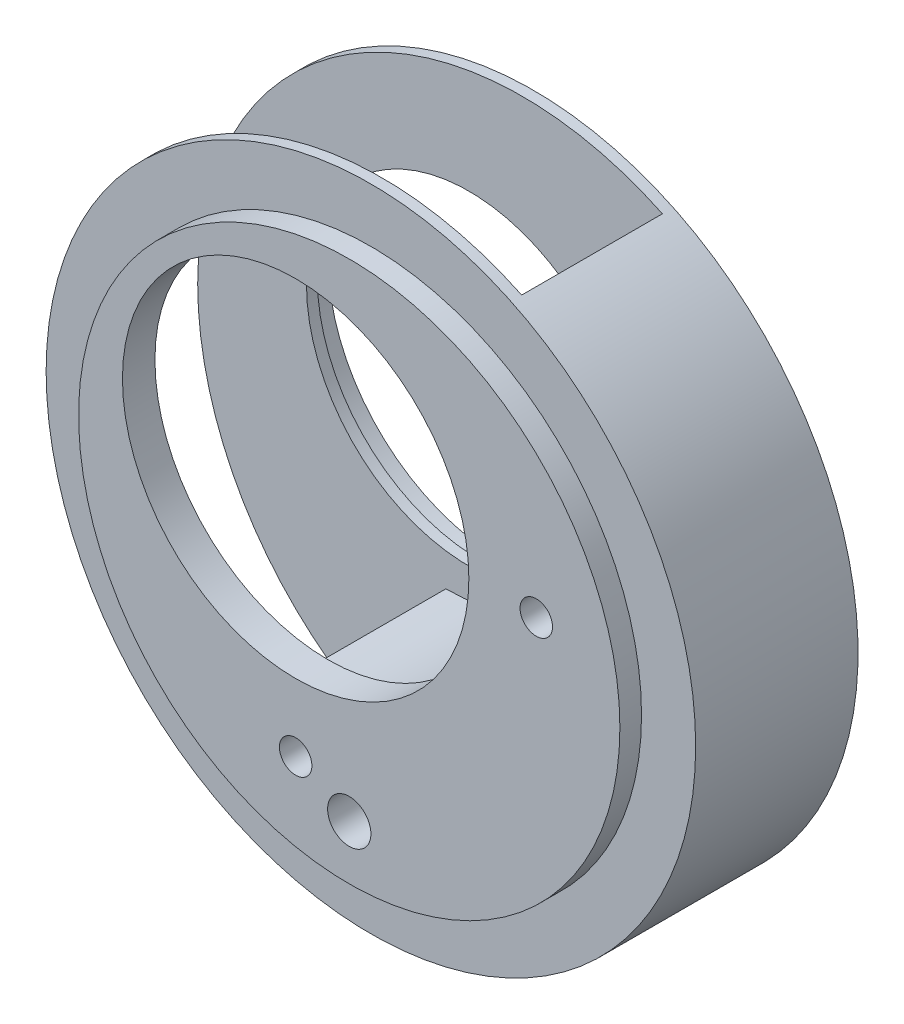
SolidWorks part; units mm, degrees
ref_plane "前视基准面" through (0, 0, 0) normal (0, 0, 1) x (1, 0, 0)
ref_plane "上视基准面" through (0, 0, 0) normal (0, 1, 0) x (1, 0, 0)
ref_plane "右视基准面" through (0, 0, 0) normal (1, 0, 0) x (0, 0, -1)
sketch "Sketch1" plane through (0, 0, 0) normal (0, 0, 1) x (1, 0, 0)
  circle A0 centre (0, 0) radius 30
  dimension "D1" = 60
extrude "Boss-Extrude1" add sketch "Sketch1" along normal blind 19
sketch "Sketch2" plane through (0, 0, 19) normal (0, 0, 1) x (1, 0, 0)
  circle A0 centre (0, 0) radius 25
  circle A1 centre (0, 0) radius 30
  dimension "D1" = 60
extrude "Cut-Extrude1" cut sketch "Sketch2" against normal blind 2
sketch "Sketch3" plane through (0, 0, 0) normal (0, 0, -1) x (-1, 0, 0)
  circle A0 centre (0, 0) radius 25
  circle A1 centre (0, 0) radius 30
  dimension "D1" = 60
extrude "Cut-Extrude2" cut sketch "Sketch3" against normal blind 2
ref_plane "Plane1" through (0, 0, 9.5) normal (0, 0, 1) x (1, 0, 0)
sketch "Sketch10" plane through (0, 0, 9.5) normal (0, 0, 1) x (1, 0, 0)
  line L0 (30, 0) -> (0, -30) construction
  line L1 (19.0896, -19.0896) -> (7.0711, -7.0711) construction
  line L3 (-7.0711, -12.9289) -> (-7.0711, -29.1548)
  line L4 (7.0711, 21.2132) -> (12.9289, 27.0711)
  circle A0 centre (0, 0) radius 30 construction
  arc A2 (-7.0711, -12.9289) -> (7.0711, 21.2132) centre (-7.0711, 7.0711) ccw
  arc A4 (12.9289, 27.0711) -> (-7.0711, -29.1548) centre (0, 0) ccw
extrude "Cut-Extrude3" cut sketch "Sketch10" against normal mid plane 13
sketch "Sketch11" plane through (0, 0, 19) normal (0, 0, 1) x (1, 0, 0)
  line L0 (25, 0) -> (0, -25) construction
  line L1 (16.6547, -16.6547) -> (-21.2132, 21.2132) construction
  circle A0 centre (0, 0) radius 25 construction
  circle A1 centre (0, 0) radius 25 construction
  circle A2 centre (0, 0) radius 30 construction
  circle A3 centre (-4.9497, 4.9497) radius 16
  dimension "D1" = 32
  dimension "D2" = 23
extrude "Cut-Extrude4" cut sketch "Sketch11" against normal up to next
sketch "Sketch12" plane through (0, 0, 0) normal (0, 0, -1) x (-1, 0, 0)
  line L0 (-25, 0) -> (0, -25) construction
  line L1 (-14.9065, -14.9065) -> (21.2132, 21.2132) construction
  circle A0 centre (0, 0) radius 25 construction
  circle A1 centre (0, 0) radius 25 construction
  circle A2 centre (0, 0) radius 30 construction
  circle A3 centre (4.9497, 4.9497) radius 15
  dimension "D1" = 23
extrude "Cut-Extrude5" cut sketch "Sketch12" against normal up to next
sketch "Sketch13" plane through (0, 0, 0) normal (0, 0, -1) x (-1, 0, 0)
  circle A0 centre (4.9497, 4.9497) radius 16
extrude "Cut-Extrude6" cut sketch "Sketch13" against normal blind 2
sketch "Sketch14" plane through (0, 0, 19) normal (0, 0, 1) x (1, 0, 0)
  circle A0 centre (0, -20) radius 2
  circle A1 centre (0, 0) radius 25 construction
  dimension "D1" = 20
extrude "Cut-Extrude7" cut sketch "Sketch14" against normal blind 3
sketch "Sketch15" plane through (0, 0, 19) normal (0, 0, 1) x (1, 0, 0)
  line L0 (-4.9497, -10.0503) -> (-4.9497, -24.5051) construction
  line L1 (10.0503, 4.9497) -> (24.5051, 4.9497) construction
  line L2 (25, 0) -> (0, -25) construction
  line L3 (15.3756, -15.3756) -> (-21.2132, 21.2132) construction
  circle A0 centre (-4.9497, 4.9497) radius 15 construction
  circle A1 centre (0, 0) radius 25 construction
  circle A2 centre (-4.9497, -17.2777) radius 1.5
  circle A3 centre (0, 0) radius 25 construction
  circle A5 centre (0, 0) radius 25 construction
  circle A6 centre (0, 0) radius 30 construction
  circle A7 centre (-4.9497, 4.9497) radius 15
  circle A8 centre (17.2777, 4.9497) radius 1.5
extrude "Cut-Extrude8" cut sketch "Sketch15" against normal blind 3
